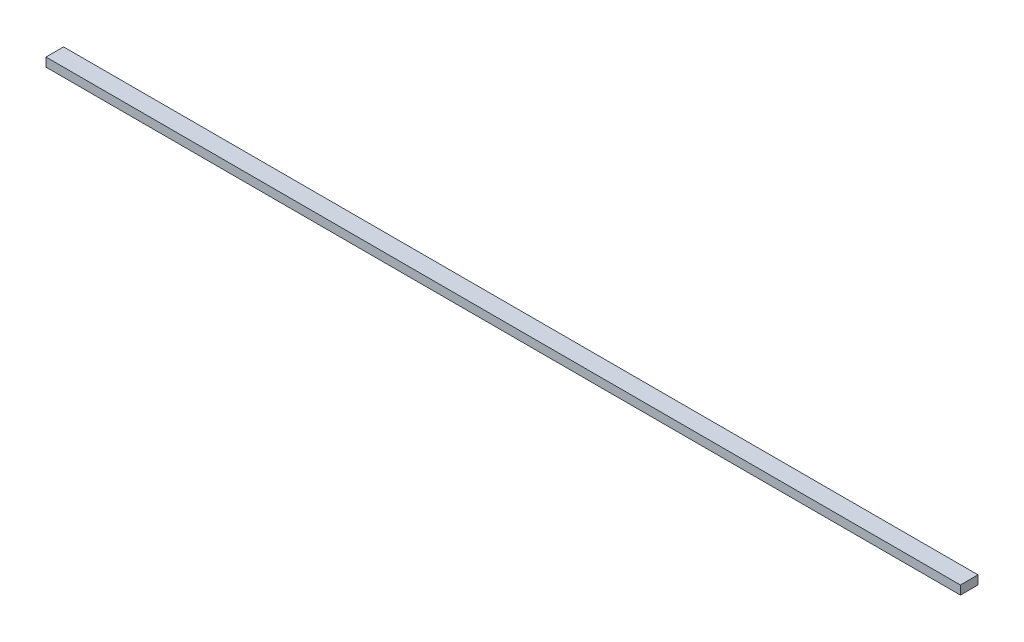
SolidWorks part; units mm, degrees
ref_plane "前视基准面" through (0, 0, 0) normal (0, 0, 1) x (1, 0, 0)
ref_plane "上视基准面" through (0, 0, 0) normal (0, 1, 0) x (1, 0, 0)
ref_plane "右视基准面" through (0, 0, 0) normal (1, 0, 0) x (0, 0, -1)
sketch "草图1" plane through (0, 0, 0) normal (0, 1, 0) x (1, 0, 0)
  line L1 (-407.4996, 218.5822) -> (1464.5004, 218.5822)
  line L2 (-407.4996, 218.5822) -> (-407.4996, 182.5822)
  line L3 (-407.4996, 182.5822) -> (1464.5004, 182.5822)
  line L4 (1464.5004, 218.5822) -> (1464.5004, 182.5822)
  dimension "D1" = 1872
  dimension "D2" = 36
extrude "凸台-拉伸1" add sketch "草图1" along normal blind 18
